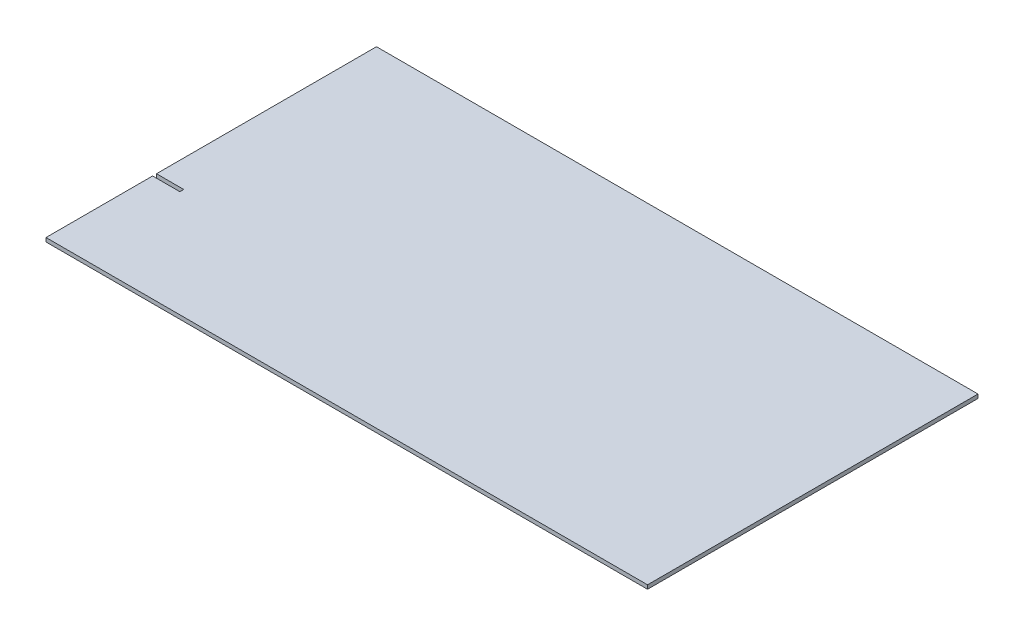
SolidWorks part; units mm, degrees
ref_plane "Front Plane" through (0, 0, 0) normal (0, 0, 1) x (1, 0, 0)
ref_plane "Top Plane" through (0, 0, 0) normal (0, 1, 0) x (1, 0, 0)
ref_plane "Right Plane" through (0, 0, 0) normal (1, 0, 0) x (0, 0, -1)
sketch "Sketch1" plane through (0, 0, 0) normal (0, 1, 0) x (1, 0, 0)
  line L1 (0, 0) -> (309, 0)
  line L2 (0, 0) -> (0, 169.76)
  line L3 (0, 169.76) -> (309, 169.76)
  line L6 (309, 169.76) -> (309, 0)
  point P6 (309, 0)
  point P7 (308.2356, 0)
  point P8 (0, 0)
  dimension "D1" = 309
  dimension "D2" = 169.76
extrude "Boss-Extrude1" add sketch "Sketch1" along normal blind 2
sketch "Sketch2" plane through (0, 2, 0) normal (0, 1, 0) x (1, 0, 0)
  line L0 (0, 169.76) -> (0, 0) construction
  line L1 (0, 56.76) -> (14, 56.76)
  line L2 (0, 56.76) -> (0, 54.76)
  line L3 (0, 54.76) -> (14, 54.76)
  line L4 (14, 56.76) -> (14, 54.76)
  line L5 (309, 169.76) -> (0, 169.76) construction
  dimension "D1" = 2
  dimension "D2" = 14
  dimension "D3" = 113
extrude "Cut-Extrude1" cut sketch "Sketch2" against normal blind 10
